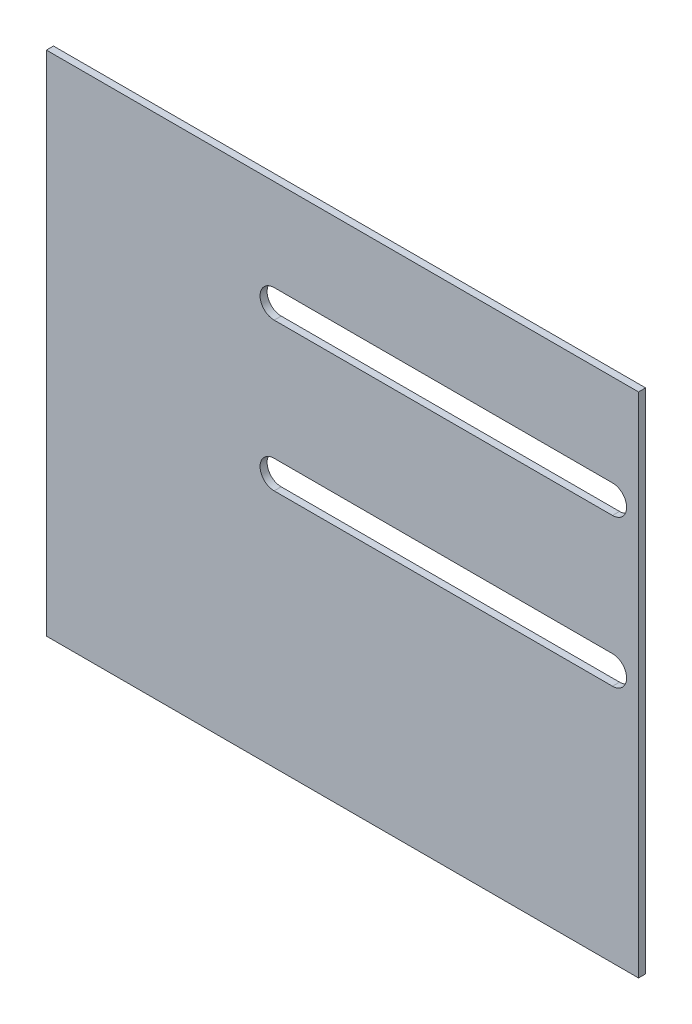
SolidWorks part; units mm, degrees
material "ABS PC"
ref_plane "Front Plane" through (0, 0, 0) normal (0, 0, 1) x (1, 0, 0)
ref_plane "Top Plane" through (0, 0, 0) normal (0, 1, 0) x (1, 0, 0)
ref_plane "Right Plane" through (0, 0, 0) normal (1, 0, 0) x (0, 0, -1)
sketch "Sketch1" plane through (0, 0, 0) normal (0, 0, 1) x (1, 0, 0)
  line L0 (0, -228.6) -> (0, 228.6) construction
  line L1 (-266.7, 228.6) -> (266.7, 228.6)
  line L2 (-266.7, 228.6) -> (-266.7, -228.6)
  line L3 (-266.7, -228.6) -> (266.7, -228.6)
  line L4 (266.7, 228.6) -> (266.7, -228.6)
  line L5 (-266.7, 228.6) -> (266.7, -228.6) construction
  line L6 (-266.7, -228.6) -> (266.7, 228.6) construction
  line L7 (-266.7, 0) -> (266.7, 0)
  line L8 (-266.7, 133.2022) -> (266.7, 133.2022) construction
  line L9 (-61.548, 133.2022) -> (243.252, 133.2022)
  line L10 (-61.548, 133.2022) -> (243.252, 133.2022) construction
  line L11 (-61.548, 145.9022) -> (243.252, 145.9022)
  line L12 (-61.548, 120.5022) -> (243.252, 120.5022)
  line L13 (-61.548, 133.2022) -> (-61.548, 0) construction
  line L14 (-61.548, 0) -> (243.252, 0) construction
  line L15 (-61.548, 0) -> (243.252, 0) construction
  line L16 (-61.548, 12.7) -> (243.252, 12.7)
  line L17 (-61.548, -12.7) -> (243.252, -12.7)
  arc A0 (-61.548, 145.9022) -> (-61.548, 120.5022) centre (-61.548, 133.2022) ccw
  arc A1 (243.252, 120.5022) -> (243.252, 145.9022) centre (243.252, 133.2022) ccw
  arc A2 (-61.548, 12.7) -> (-61.548, -12.7) centre (-61.548, 0) ccw
  arc A3 (243.252, -12.7) -> (243.252, 12.7) centre (243.252, 0) ccw
  point P0 (0, 0)
  point P12 (90.852, 133.2022)
  point P15 (90.852, 133.2022)
  point P22 (90.852, 0)
  dimension "D1" = 457.2
  dimension "D2" = 533.4
  dimension "D3" = 304.8
extrude "Boss-Extrude4" add sketch "Sketch1" along normal blind 6.35 contours L2 L1 L4 L3 | L12 A1 L11 A0 | L17 A3 L16 A2
sketch "Sketch3" plane through (0, 0, 0) normal (0, 0, -1) x (-1, 0, 0)
